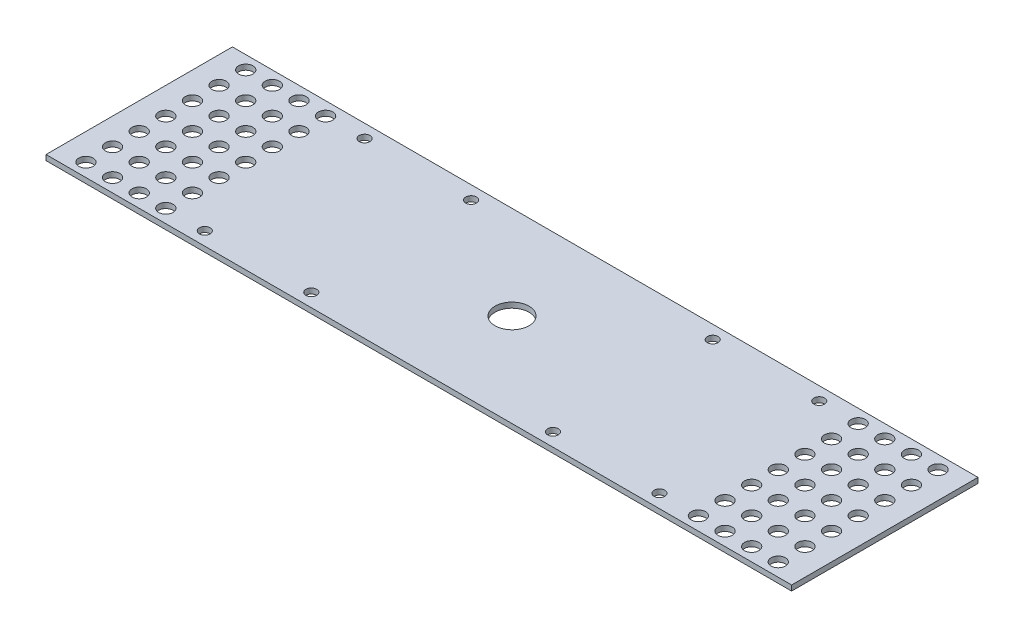
SolidWorks part; units mm, degrees
ref_plane "Front Plane" through (0, 0, 0) normal (0, 0, 1) x (1, 0, 0)
ref_plane "Top Plane" through (0, 0, 0) normal (0, 1, 0) x (1, 0, 0)
ref_plane "Right Plane" through (0, 0, 0) normal (1, 0, 0) x (0, 0, -1)
sketch "Sketch1" plane through (0, 0, 0) normal (0, 1, 0) x (1, 0, 0)
  line L1 (-177.8, -457.2) -> (177.8, -457.2)
  line L2 (-177.8, -457.2) -> (-177.8, 152.4)
  line L3 (-177.8, 152.4) -> (177.8, 152.4)
  line L4 (177.8, -457.2) -> (177.8, 152.4)
  point P0 (0, 0)
  point P7 (0, 152.4)
  dimension "D1" = 609.6
  dimension "D2" = 355.6
  dimension "D8" = 152.4
extrude "Boss-Extrude1" add sketch "Sketch1" along normal blind 2.54
sketch "Sketch2" plane through (0, 2.54, 0) normal (0, 1, 0) x (1, 0, 0)
  line L1 (0, 0) -> (0, -76.2) construction
  line L2 (0, -38.1) -> (47.2581, -38.1) construction
  line L3 (177.8, -457.2) -> (177.8, 152.4) construction
  line L4 (-177.8, 152.4) -> (177.8, 152.4)
  line L5 (-177.8, 152.4) -> (-177.8, 6.35)
  line L6 (-177.8, 6.35) -> (177.8, 6.35)
  line L7 (177.8, 152.4) -> (177.8, 6.35)
  line L8 (-177.8, 152.4) -> (-177.8, -457.2) construction
  line L9 (-177.8, -457.2) -> (177.8, -457.2)
  line L10 (-177.8, -457.2) -> (-177.8, -82.55)
  line L11 (-177.8, -82.55) -> (177.8, -82.55)
  line L12 (177.8, -457.2) -> (177.8, -82.55)
  circle A0 centre (-108.4224, 0) radius 2.5527
  circle A1 centre (-57.6224, 0) radius 2.5527
  circle A2 centre (-57.6224, -76.2) radius 2.5527
  circle A3 centre (-108.4224, -76.2) radius 2.5527
  circle A4 centre (108.4224, -76.2) radius 2.5527
  circle A5 centre (57.6224, -76.2) radius 2.5527
  circle A6 centre (57.6224, 0) radius 2.5527
  circle A7 centre (108.4224, 0) radius 2.5527
  circle A104 centre (-139.7, 0) radius 3.429
  circle A105 centre (-127, 0) radius 3.429
  circle A106 centre (-139.7, -12.7) radius 3.429
  circle A107 centre (-127, -12.7) radius 3.429
  circle A108 centre (-139.7, -25.4) radius 3.429
  circle A109 centre (-127, -25.4) radius 3.429
  circle A110 centre (-139.7, -38.1) radius 3.429
  circle A111 centre (-127, -38.1) radius 3.429
  circle A112 centre (-139.7, -50.8) radius 3.429
  circle A113 centre (-127, -50.8) radius 3.429
  circle A114 centre (-139.7, -63.5) radius 3.429
  circle A115 centre (-165.1, 0) radius 3.429
  circle A116 centre (-152.4, 0) radius 3.429
  circle A117 centre (-152.4, -12.7) radius 3.429
  circle A118 centre (-152.4, -25.4) radius 3.429
  circle A119 centre (-152.4, -38.1) radius 3.429
  circle A120 centre (-152.4, -50.8) radius 3.429
  circle A121 centre (-152.4, -63.5) radius 3.429
  circle A122 centre (-152.4, -76.2) radius 3.429
  circle A123 centre (-165.1, -12.7) radius 3.429
  circle A124 centre (-165.1, -25.4) radius 3.429
  circle A125 centre (-165.1, -38.1) radius 3.429
  circle A126 centre (-165.1, -50.8) radius 3.429
  circle A127 centre (-165.1, -63.5) radius 3.429
  circle A128 centre (-165.1, -76.2) radius 3.429
  circle A143 centre (-127, -63.5) radius 3.429
  circle A144 centre (-139.7, -76.2) radius 3.429
  circle A145 centre (-127, -76.2) radius 3.429
  circle A146 centre (127, -76.2) radius 3.429
  circle A147 centre (139.7, -76.2) radius 3.429
  circle A148 centre (127, -63.5) radius 3.429
  circle A149 centre (165.1, -76.2) radius 3.429
  circle A150 centre (165.1, -63.5) radius 3.429
  circle A151 centre (165.1, -50.8) radius 3.429
  circle A152 centre (165.1, -38.1) radius 3.429
  circle A153 centre (165.1, -25.4) radius 3.429
  circle A154 centre (165.1, -12.7) radius 3.429
  circle A155 centre (152.4, -76.2) radius 3.429
  circle A156 centre (152.4, -63.5) radius 3.429
  circle A157 centre (152.4, -50.8) radius 3.429
  circle A158 centre (152.4, -38.1) radius 3.429
  circle A159 centre (152.4, -25.4) radius 3.429
  circle A160 centre (152.4, -12.7) radius 3.429
  circle A161 centre (152.4, 0) radius 3.429
  circle A162 centre (165.1, 0) radius 3.429
  circle A163 centre (139.7, -63.5) radius 3.429
  circle A164 centre (127, -50.8) radius 3.429
  circle A165 centre (139.7, -50.8) radius 3.429
  circle A166 centre (127, -38.1) radius 3.429
  circle A167 centre (139.7, -38.1) radius 3.429
  circle A168 centre (127, -25.4) radius 3.429
  circle A169 centre (139.7, -25.4) radius 3.429
  circle A170 centre (127, -12.7) radius 3.429
  circle A171 centre (139.7, -12.7) radius 3.429
  circle A172 centre (127, 0) radius 3.429
  circle A173 centre (139.7, 0) radius 3.429
  dimension "D1" = 5.1054
  dimension "D7" = 6.858
  dimension "D2" = 50.8
  dimension "D3" = 2
  dimension "D5" = 108.4224
  dimension "D6" = 76.2
  dimension "D8" = 12.7
  dimension "D9" = 4
  dimension "D12" = 6.35
  dimension "D13" = 82.55
  dimension "D4" = 2
  dimension "D10" = 7
extrude "Cut-Extrude1" cut sketch "Sketch2" against normal through all
sketch "Sketch3" plane through (0, 2.54, 0) normal (0, 1, 0) x (1, 0, 0)
  line L0 (0, 6.35) -> (0, -82.55) construction
  line L1 (-177.8, 6.35) -> (177.8, 6.35) construction
  line L2 (177.8, -82.55) -> (-177.8, -82.55) construction
  circle A0 centre (0, -38.1) radius 8.1013
  point P2 (0, -52.0927)
extrude "Cut-Extrude2" cut sketch "Sketch3" against normal through all
